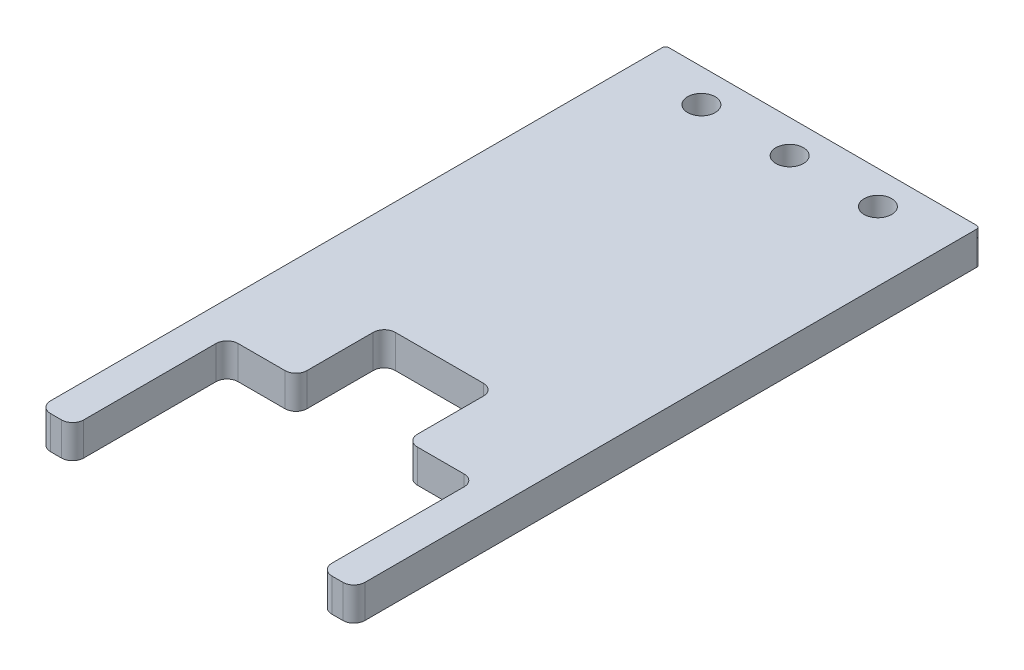
SolidWorks part; units mm, degrees
ref_plane "Front" through (0, 0, 0) normal (0, 0, 1) x (1, 0, 0)
ref_plane "Top" through (0, 0, 0) normal (0, 1, 0) x (1, 0, 0)
ref_plane "Right" through (0, 0, 0) normal (1, 0, 0) x (0, 0, -1)
sketch "Sketch1" plane through (0, 0, 0) normal (0, 1, 0) x (1, 0, 0)
  line L0 (0, 42.75) -> (0, 0)
  line L1 (0, 0) -> (28.5, 0)
  line L3 (0, 42.75) -> (28.5, 42.75)
  line L4 (28.5, 0) -> (28.5, 42.75)
  dimension "D1" = 28.5
  dimension "D2" = 42.75
extrude "Boss-Extrude1" add sketch "Sketch1" along normal blind 3
hole_wizard "M3x0.5 Tapped Hole1" positions "Sketch5" profile "Sketch4" tap size "M3x0.5" standard "ANSI Metric" end condition through all
sketch "Sketch5" plane through (0, 0, 0) normal (0, -1, 0) x (-1, 0, 0)
  line L0 (-28.5, 42.75) -> (0, 42.75) construction
  line L1 (-28.5, 42.75) -> (0, 42.75) construction
  line L2 (-28.5, 39.75) -> (-22.25, 39.75) construction
  line L3 (-28.5, 0) -> (-28.5, 42.75) construction
  line L4 (-22.25, 39.75) -> (-14.25, 39.75) construction
  line L5 (-14.25, 39.75) -> (-6.25, 39.75) construction
  line L6 (-6.25, 39.75) -> (0, 39.75) construction
  line L7 (0, 42.75) -> (0, 0) construction
  point P0 (-22.25, 39.75)
  point P2 (-14.25, 39.75)
  point P4 (-6.25, 39.75)
  point P9 (-14.25, 42.75)
  dimension "D1" = 3
  dimension "D2" = 8
cosmetic thread "Hole Thread1" parameters "D2"=3
cosmetic thread "Hole Thread2" parameters "D2"=3
cosmetic thread "Hole Thread3" parameters "D2"=3
sketch "Sketch4" plane through (22.25, 0, -39.75) normal (1, 0, 0) x (0, 0, -1)
  line L0 (0, 0) -> (0, 3)
  line L1 (0, 3) -> (1.25, 3)
  line L2 (1.25, 3) -> (1.25, 0)
  line L5 (1.25, 0) -> (0, 0)
  line L11 (0, -6.35) -> (0, 107.95) construction
  dimension "Thru Tap Drill Dia." = 2.5
  dimension "Thru Tap Drill Depth" = 3
sketch "Sketch6" plane through (0, 3, 0) normal (0, 1, 0) x (1, 0, 0)
  line L9 (0, 0) -> (0, -14)
  line L10 (0, -14) -> (3, -14)
  line L11 (3, -14) -> (3, 0)
  line L12 (0, 0) -> (28.5, 0) construction
  line L13 (3, 0) -> (0, 0)
  line L14 (14.25, 42.75) -> (14.25, 0) construction
  line L15 (28.5, 42.75) -> (0, 42.75) construction
  line L16 (25.5, 0) -> (28.5, 0)
  line L17 (25.5, -14) -> (25.5, 0)
  line L18 (28.5, -14) -> (25.5, -14)
  line L19 (28.5, 0) -> (28.5, -14)
  dimension "D1" = 3
  dimension "D2" = 14
extrude "Boss-Extrude2" add sketch "Sketch6" against normal up to surface (3 mm away) up to face at (22.25, 0, -41)
sketch "Sketch7" plane through (0, 3, 0) normal (0, 1, 0) x (1, 0, 0)
  line L0 (3, 0) -> (25.5, 0) construction
  line L2 (9.25, 0) -> (9.25, 8)
  line L3 (9.25, 8) -> (19.25, 8)
  line L4 (19.25, 0) -> (19.25, 8)
  line L5 (14.25, 0) -> (14.25, 8) construction
  line L7 (9.25, 0) -> (19.25, 0)
  point P0 (14.25, 0)
  dimension "D1" = 10
  dimension "D2" = 8
extrude "Cut-Extrude1" cut sketch "Sketch7" against normal through all
fillet "Fillet1" radius 1 10 edges at (0, 1.5, 14) (28.5, 1.5, 14) (25.5, 1.5, 14) (3, 1.5, 14) (25.5, 1.5, 0) (3, 1.5, 0) (19.25, 1.5, 0) (19.25, 1.5, -8) (9.25, 1.5, -8) (9.25, 1.5, 0)
fillet "Fillet2" radius 0.3 2 edges at (28.5, 1.5, -42.75) (0, 1.5, -42.75)
equation "\"plunger_width\"= 28.5mm"
equation "\"D1@Sketch1\"=\"plunger_width\""
equation "\"arm_width\"= 37mm"
